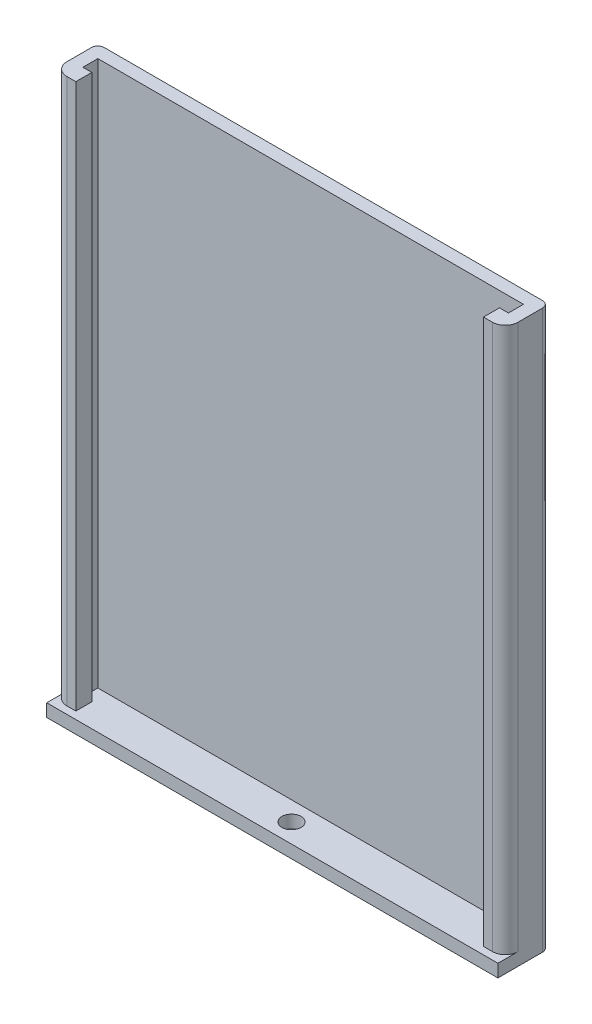
SolidWorks part; units mm, degrees
ref_plane "Ön Düzlem" through (0, 0, 0) normal (0, 0, 1) x (1, 0, 0)
ref_plane "Üst Düzlem" through (0, 0, 0) normal (0, 1, 0) x (1, 0, 0)
ref_plane "Sağ Düzlem" through (0, 0, 0) normal (1, 0, 0) x (0, 0, -1)
sketch "Çizim1" plane through (0, 0, 0) normal (0, 0, 1) x (1, 0, 0)
  line L1 (0, 0) -> (66.6, 0)
  line L2 (0, 0) -> (0, 83)
  line L3 (0, 83) -> (66.6, 83)
  line L4 (66.6, 0) -> (66.6, 83)
  dimension "D1" = 66.6
  dimension "D2" = 83
extrude "Yükseklik-Ekstrüzyon1" add sketch "Çizim1" along normal blind 2
sketch "Çizim2" plane through (0, 83, 0) normal (0, 1, 0) x (1, 0, 0)
  line L0 (66.6, -2) -> (0, -2) construction
  line L1 (0, 0) -> (-1, 0)
  line L2 (0, 0) -> (0, -4.35)
  line L3 (33.3, 0) -> (33.3, -2) construction
  line L4 (-2, -1) -> (-2, -4.85)
  line L5 (0, -4.35) -> (1.4, -4.35)
  line L6 (66.6, 0) -> (0, 0) construction
  line L7 (0, -6.85) -> (1.4, -6.85)
  line L8 (1.4, -4.35) -> (1.4, -6.85)
  line L9 (65.2, -4.35) -> (65.2, -6.85)
  line L10 (66.6, -6.85) -> (65.2, -6.85)
  line L11 (66.6, -4.35) -> (65.2, -4.35)
  line L12 (68.6, -1) -> (68.6, -4.85)
  line L13 (66.6, 0) -> (66.6, -4.35)
  line L14 (66.6, 0) -> (67.6, 0)
  arc A0 (0, -6.85) -> (-2, -4.85) centre (0, -4.85) cw
  arc A1 (-2, -1) -> (-1, 0) centre (-1, -1) cw
  arc A2 (68.6, -1) -> (67.6, 0) centre (67.6, -1) ccw
  arc A3 (66.6, -6.85) -> (68.6, -4.85) centre (66.6, -4.85) ccw
  point P14 (-2, 0)
  point P28 (68.6, 0)
  dimension "D5" = 2
  dimension "D6" = 1
  dimension "D1" = 2
  dimension "D2" = 2.35
  dimension "D3" = 1.4
  dimension "D4" = 2.5
extrude "Yükseklik-Ekstrüzyon2" add sketch "Çizim2" against normal up to vertex (83 mm away)
sketch "Çizim4" plane through (0, 0, 0) normal (0, -1, 0) x (1, 0, 0)
  line L12 (-1, 0) -> (67.6, 0)
  line L13 (68.6, 1) -> (68.6, 4.85)
  line L14 (66.6, 6.85) -> (65.2, 6.85)
  line L15 (65.2, 6.85) -> (65.2, 4.35)
  line L16 (65.2, 4.35) -> (66.6, 4.35)
  line L17 (66.6, 4.35) -> (66.6, 2)
  line L18 (66.6, 2) -> (0, 2)
  line L19 (0, 2) -> (0, 4.35)
  line L20 (0, 4.35) -> (1.4, 4.35)
  line L21 (1.4, 4.35) -> (1.4, 6.85)
  line L22 (1.4, 6.85) -> (0, 6.85)
  line L23 (-2, 4.85) -> (-2, 1)
  line L24 (-1, 0) -> (67.6, 0)
  line L25 (68.6, 1) -> (68.6, 4.85)
  line L26 (66.6, 6.85) -> (65.2, 6.85)
  line L27 (65.2, 6.85) -> (65.2, 4.35)
  line L28 (65.2, 4.35) -> (66.6, 4.35)
  line L29 (66.6, 4.35) -> (66.6, 2)
  line L30 (66.6, 2) -> (0, 2)
  line L31 (0, 2) -> (0, 4.35)
  line L32 (0, 4.35) -> (1.4, 4.35)
  line L33 (1.4, 4.35) -> (1.4, 6.85)
  line L34 (1.4, 6.85) -> (0, 6.85)
  line L35 (-2, 4.85) -> (-2, 1)
  arc A4 (67.6, 0) -> (68.6, 1) centre (67.6, 1) ccw
  arc A5 (68.6, 4.85) -> (66.6, 6.85) centre (66.6, 4.85) ccw
  arc A6 (0, 6.85) -> (-2, 4.85) centre (0, 4.85) ccw
  arc A7 (-2, 1) -> (-1, 0) centre (-1, 1) ccw
  arc A8 (67.6, 0) -> (68.6, 1) centre (67.6, 1) ccw
  arc A9 (68.6, 4.85) -> (66.6, 6.85) centre (66.6, 4.85) ccw
  arc A10 (0, 6.85) -> (-2, 4.85) centre (0, 4.85) ccw
  arc A11 (-2, 1) -> (-1, 0) centre (-1, 1) ccw
  dimension "D1" = 0
extrude "Yükseklik-Ekstrüzyon3" add sketch "Çizim4" along normal blind 2.3
sketch "Çizim5" plane through (0, -2.3, 0) normal (0, -1, 0) x (1, 0, 0)
  line L0 (-1, 0) -> (67.6, 0) construction
  line L1 (67.6, 0) -> (-1, 0)
  line L2 (68.6, 1) -> (68.6, 8)
  line L3 (68.6, 8) -> (-2, 8)
  line L4 (-2, 1) -> (-2, 8)
  line L5 (-2, 4.85) -> (-2, 1) construction
  line L6 (68.6, 1) -> (68.6, 4.85) construction
  arc A0 (-2, 1) -> (-1, 0) centre (-1, 1) ccw
  arc A1 (68.6, 1) -> (67.6, 0) centre (67.6, 1) cw
  dimension "D1" = 1
  dimension "D2" = 1
  dimension "D3" = 8
extrude "Yükseklik-Ekstrüzyon4" add sketch "Çizim5" along normal blind 2
sketch "Çizim6" plane through (0, -4.3, 0) normal (0, -1, 0) x (1, 0, 0)
  line L0 (68.6, 5) -> (-2, 5) construction
  line L1 (68.6, 1) -> (68.6, 8) construction
  line L2 (-2, 8) -> (-2, 1) construction
  line L3 (68.6, 8) -> (-2, 8) construction
  circle A0 centre (33.3, 5) radius 1.5
  dimension "D1" = 3
  dimension "D2" = 3
extrude "Kes-Ekstrüzyon2" cut sketch "Çizim6" against normal blind 4
